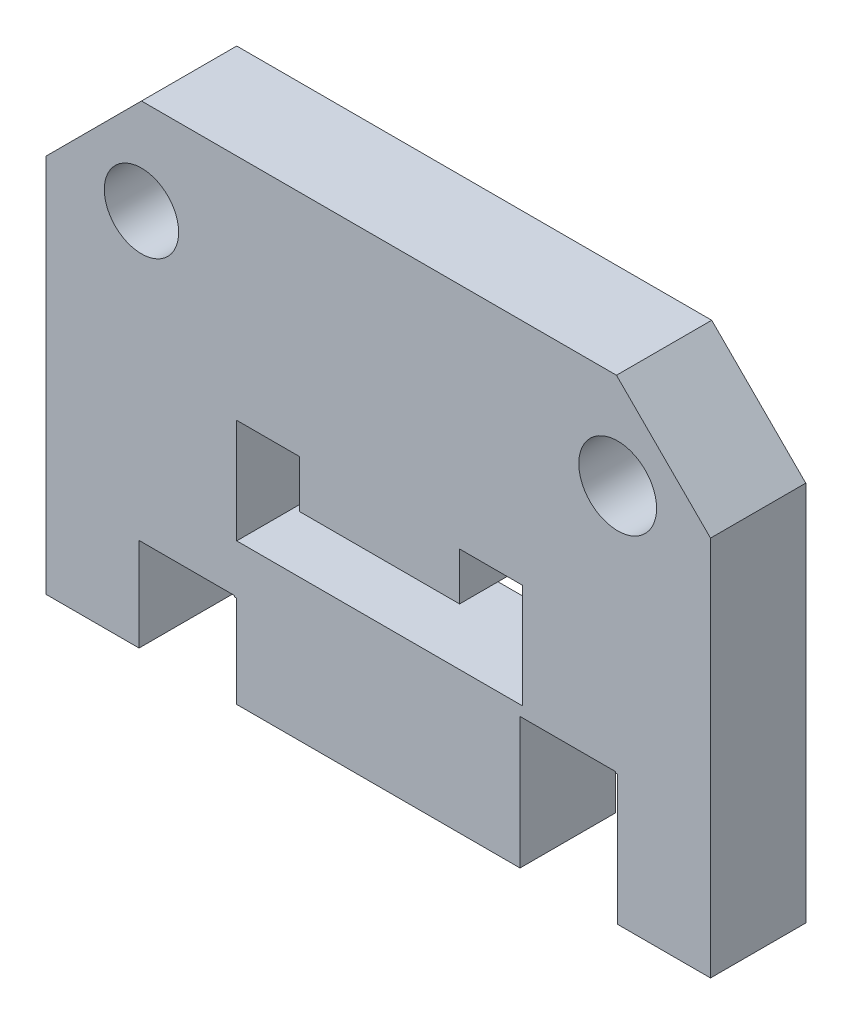
SolidWorks part; units mm, degrees
ref_plane "Front Plane" through (0, 0, 0) normal (0, 0, 1) x (1, 0, 0)
ref_plane "Top Plane" through (0, 0, 0) normal (0, 1, 0) x (1, 0, 0)
ref_plane "Right Plane" through (0, 0, 0) normal (1, 0, 0) x (0, 0, -1)
sketch "Sketch1" plane through (0, 0, 0) normal (0, 0, 1) x (1, 0, 0)
  line L0 (-62.7794, 0) -> (-40.0728, 0) construction
  line L1 (-25, 25) -> (25, 25)
  line L2 (-35, 15) -> (-35, -25)
  line L3 (-35, -25) -> (-25, -25)
  line L4 (35, 15) -> (35, -25)
  line L5 (-35, 25) -> (-29.1667, 20.8333) construction
  line L6 (-35, -25) -> (-21.2939, -15.2099) construction
  line L7 (0.0511, 0) -> (0.0511, 25) construction
  line L8 (-35, 15) -> (-25, 25)
  line L9 (25, 25) -> (35, 15)
  line L10 (-25, -25) -> (-25, -15.2099)
  line L11 (-25, -15.2099) -> (-15, -15.2099)
  line L12 (-15, -15.2099) -> (-15, -25)
  line L13 (15, -25) -> (15, -11.2156)
  line L14 (15, -11.2156) -> (25, -11.2156)
  line L15 (25, -11.2156) -> (25, -25)
  line L16 (-15, -25) -> (15, -25)
  line L17 (25, -25) -> (35, -25)
  line L23 (0.0511, 66.8061) -> (0.0511, -0.0365) construction
  line L24 (0, 0) -> (0.0511, 0) construction
  line L27 (14, 10) -> (15, 10)
  line L28 (0.0511, 0.0365) -> (0.0511, -0.0365) construction
  line L29 (0, 0) -> (0.0511, 0) construction
  line L30 (0, 0) -> (0.0511, -0.0365) construction
  line L31 (29.1667, 20.8333) -> (35, 25) construction
  line L33 (35, 0) -> (62.8817, 0) construction
  line L34 (15.7018, -11.2156) -> (35, -25) construction
  line L36 (0.0511, -25) -> (0.0511, -10.3262) construction
  line L37 (0, 0) -> (0.0511, 0.0365) construction
  line L38 (0, 0) -> (0.0511, 0) construction
  line L41 (0, 0) -> (0, -10) construction
  line L42 (0.0511, -25) -> (0.0511, -7.6872) construction
  line L50 (-16.172, -4.0357) -> (-7.9748, -1.9901) construction
  line L52 (-15, -10) -> (15, -10)
  line L53 (15, -10) -> (15, 0.9643)
  line L54 (8.3986, 0.9643) -> (8.3986, -4.0357)
  line L55 (8.3986, -4.0357) -> (-8.3986, -4.0357)
  line L56 (8.3986, 0.9643) -> (15, 0.9643)
  line L57 (-25.2527, 25.1263) -> (24.7473, 25.1263)
  line L58 (-35.2527, 15.1263) -> (-35.2527, -24.8737)
  line L59 (-35.2527, -24.8737) -> (-25.2527, -24.8737)
  line L60 (34.7473, 15.1263) -> (34.7473, -24.8737)
  line L61 (-35.2527, 15.1263) -> (-25.2527, 25.1263)
  line L62 (24.7473, 25.1263) -> (34.7473, 15.1263)
  line L63 (-25.2527, -24.8737) -> (-25.2527, -15.0836)
  line L64 (-25.2527, -15.0836) -> (-15.2527, -15.0836)
  line L65 (-15.2527, -15.0836) -> (-15.2527, -24.8737)
  line L66 (14.7473, -24.8737) -> (14.7473, -11.0892)
  line L67 (14.7473, -11.0892) -> (24.7473, -11.0892)
  line L68 (24.7473, -11.0892) -> (24.7473, -24.8737)
  line L69 (-15.2527, -24.8737) -> (14.7473, -24.8737)
  line L70 (24.7473, -24.8737) -> (34.7473, -24.8737)
  line L71 (-8.3986, 0.9643) -> (-8.3986, -4.0357)
  line L72 (-8.3986, 0.9643) -> (-15, 0.9643)
  line L73 (-15, -10) -> (-15, 0.9643)
  circle A0 centre (-25, 15) radius 3.9032
  circle A1 centre (25, 15) radius 4.0858
  point P0 (0, 0)
  point P10 (-74.7423, 28.6802)
  point P21 (-0.0103, 0)
  point P66 (0, -4.0357)
  dimension "D9" = 5
  dimension "D1" = 50
  dimension "D2" = 70
  dimension "D3" = 45
  dimension "D4" = 10
  dimension "D7" = 10
  dimension "D8" = 15
extrude "Boss-Extrude1" add sketch "Sketch1" along normal mid plane 10
